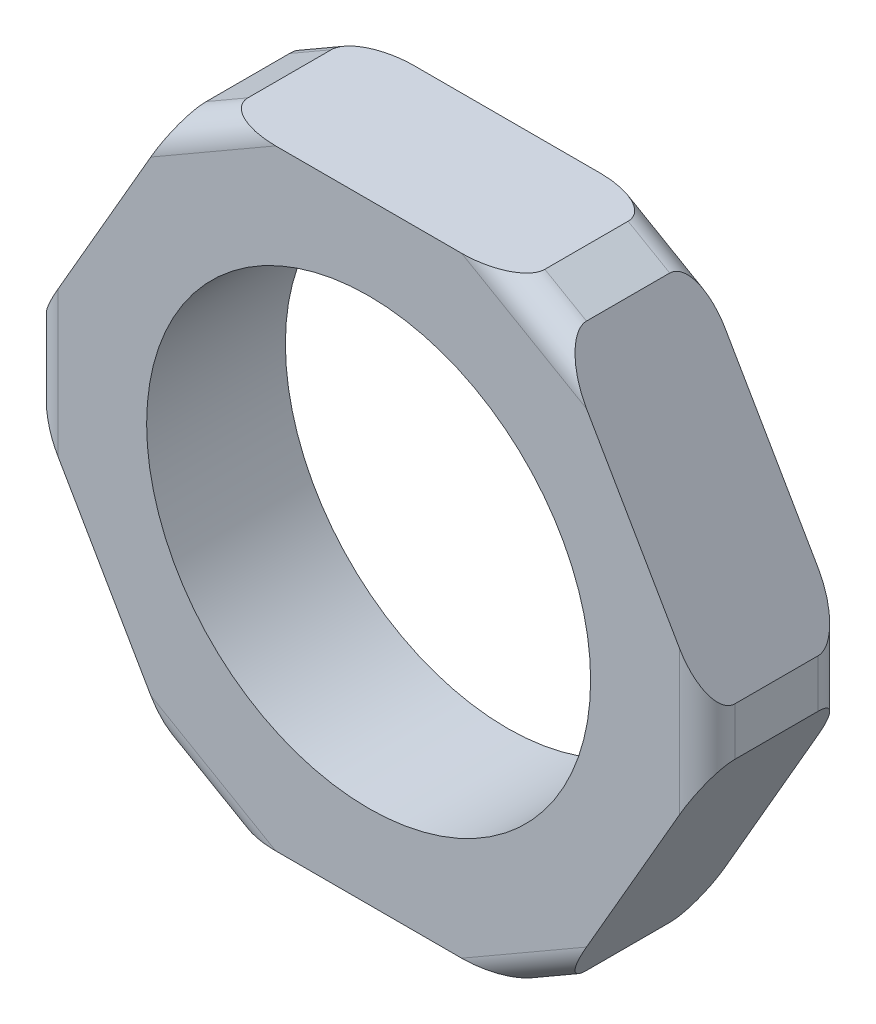
SolidWorks part; units mm, degrees
ref_plane "Front" through (0, 0, 0) normal (0, 0, 1) x (1, 0, 0)
ref_plane "Top" through (0, 0, 0) normal (0, 1, 0) x (1, 0, 0)
ref_plane "Right" through (0, 0, 0) normal (1, 0, 0) x (0, 0, -1)
sketch "Sketch1" plane through (0, 0, 0) normal (0, 0, 1) x (1, 0, 0)
  line L1 (12.7017, 0) -> (6.3509, 11)
  line L2 (6.3509, 11) -> (-6.3509, 11)
  line L3 (-6.3509, 11) -> (-12.7017, 0)
  line L4 (-12.7017, 0) -> (-6.3509, -11)
  line L5 (-6.3509, -11) -> (6.3509, -11)
  line L6 (6.3509, -11) -> (12.7017, 0)
  circle A0 centre (0, 0) radius 11 construction
  circle A1 centre (0, 0) radius 8
  dimension "D1" = 16
  dimension "D2" = 22
extrude "Boss-Extrude1" add sketch "Sketch1" along normal mid plane 5
chamfer "Chamfer1" distance 1 angle 30 6 edges at (-6.3509, 11, 0) (-12.7017, 0, 0) (-6.3509, -11, 0) (6.3509, -11, 0) (12.7017, 0, 0) (6.3509, 11, 0)
fillet "Fillet1" radius 1 12 edges at (-6.1009, 10.567, -2.5) (6.1009, 10.567, -2.5) (12.2017, 0, -2.5) (6.1009, -10.567, -2.5) (-6.1009, -10.567, -2.5) (-12.2017, 0, -2.5) (6.1009, 10.567, 2.5) (12.2017, 0, 2.5) (6.1009, -10.567, 2.5) (-6.1009, -10.567, 2.5) (-12.2017, 0, 2.5) (-6.1009, 10.567, 2.5)
